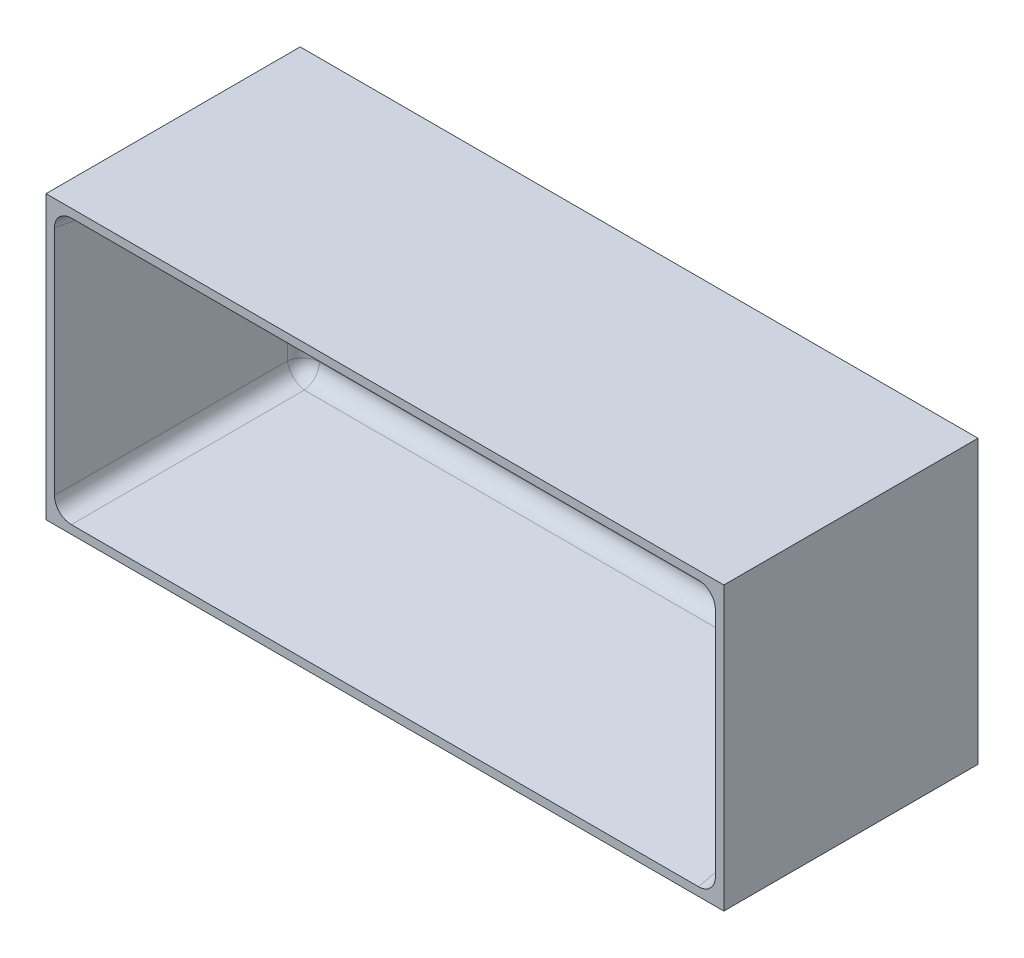
SolidWorks part; units mm, degrees
ref_plane "Front Plane" through (0, 0, 0) normal (0, 0, 1) x (1, 0, 0)
ref_plane "Top Plane" through (0, 0, 0) normal (0, 1, 0) x (1, 0, 0)
ref_plane "Right Plane" through (0, 0, 0) normal (1, 0, 0) x (0, 0, -1)
sketch "Sketch1" plane through (0, 0, 0) normal (0, 0, 1) x (1, 0, 0)
  line L5 (-60, 25) -> (60, 25)
  line L6 (-60, 25) -> (-60, -25)
  line L7 (-60, -25) -> (60, -25)
  line L8 (60, 25) -> (60, -25)
  line L9 (-60, 25) -> (60, -25) construction
  line L10 (-60, -25) -> (60, 25) construction
  point P0 (0, 0)
  dimension "D1" = 120
  dimension "D2" = 50
extrude "Boss-Extrude1" add sketch "Sketch1" along normal blind 5
sketch "Sketch2" plane through (0, 0, 5) normal (0, 0, 1) x (1, 0, 0)
  line L1 (-58.5, 23.5) -> (58.5, 23.5)
  line L2 (-58.5, 23.5) -> (-58.5, -23.5)
  line L3 (-58.5, -23.5) -> (58.5, -23.5)
  line L4 (58.5, 23.5) -> (58.5, -23.5)
  line L5 (-58.5, 23.5) -> (58.5, -23.5) construction
  line L6 (-58.5, -23.5) -> (58.5, 23.5) construction
  line L15 (60, -25) -> (60, 25)
  line L16 (60, 25) -> (-60, 25)
  line L17 (-60, 25) -> (-60, -25)
  line L18 (-60, -25) -> (60, -25)
  line L19 (60, -25) -> (60, 25)
  line L20 (60, 25) -> (-60, 25)
  line L21 (-60, 25) -> (-60, -25)
  line L22 (-60, -25) -> (60, -25)
  point P0 (0, 0)
  dimension "D1" = 0
extrude "Boss-Extrude3" add sketch "Sketch2" along normal blind 40
draft "Draft2" type of draft neutral plane draft angle 6 faces to draft 4 face at (-58.5, 0, 25) face at (0, 23.5, 25) face at (58.5, 0, 25) face at (0, -23.5, 25) neutral plane through (0, 0, 45) neutral plane normal (0, 0, 1) parameters "D1"=6
fillet "Fillet1" radius 3 8 edges at (-56.3979, -21.3979, 25) (-56.3979, 21.3979, 25) (-54.2958, 0, 5) (0, 19.2958, 5) (0, -19.2958, 5) (54.2958, 0, 5) (56.3979, -21.3979, 25) (56.3979, 21.3979, 25)
